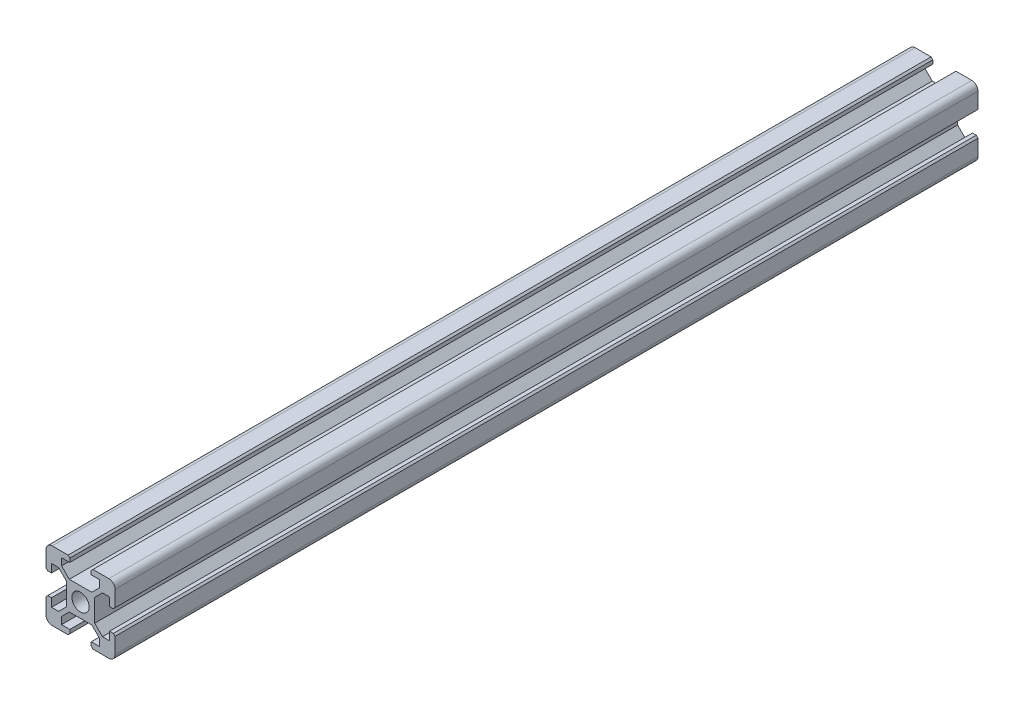
SolidWorks part; units mm, degrees
ref_plane "Front Plane" through (0, 0, 0) normal (0, 0, 1) x (1, 0, 0)
ref_plane "Top Plane" through (0, 0, 0) normal (0, 1, 0) x (1, 0, 0)
ref_plane "Right Plane" through (0, 0, 0) normal (1, 0, 0) x (0, 0, -1)
other "Default"
sketch "Sketch1" plane through (0, 0, 0) normal (0, 0, 1) x (1, 0, 0)
  line L0 (0, 4.1) -> (3.2515, 4.1)
  line L1 (3.2515, 4.1) -> (5.5, 6.3485)
  line L2 (5.5, 6.3485) -> (5.5, 8.4)
  line L3 (5.5, 8.4) -> (3.1, 8.4)
  line L4 (3.1, 8.4) -> (3.1, 9.5)
  line L5 (3.1, 9.5) -> (3.6, 10)
  line L6 (3.6, 10) -> (8.21, 10)
  line L7 (0, 0) -> (38.0854, 38.0854) construction
  line L8 (0, 0) -> (-25.3528, 25.3528) construction
  line L9 (0, 0) -> (34.3199, 0) construction
  line L10 (0, 0) -> (0, 57.4148) construction
  line L11 (1.7678, 1.7678) -> (9.4757, 9.4757)
  line L12 (0, 4.1) -> (0, 2.5)
  line L13 (10.0067, 8.9448) -> (12.1533, 6.7981) construction
  circle A0 centre (0, 0) radius 2.5 construction
  arc A1 (8.21, 10) -> (9.4757, 9.4757) centre (8.21, 8.21) cw
  arc A2 (0, 2.5) -> (1.7678, 1.7678) centre (0, 0) cw
  arc A3 (9.4757, 9.4757) -> (10, 8.21) centre (8.21, 8.21) cw construction
  dimension "HoleDiameter" = 5
  dimension "D1" = 45
  dimension "SlotWidth" = 6.2
  dimension "SlotWidthChamfer" = 7.2
  dimension "SlotHeight" = 4.3
  dimension "Width" = 20
  dimension "Height" = 20
  dimension "SlotInsideWidth" = 11
  dimension "ExtensionThickness" = 1.2
  dimension "SlotDepth" = 1.6
  dimension "D11" = 26.8014
extrude "Boss-Extrude1" add sketch "Sketch1" along normal mid plane 250
mirror "Mirror1" about plane through (1.7678, 1.7678, 125) normal (-0.7071, 0.7071, 0) of bodies 101
mirror "Mirror2" about plane through (0, 4.1, 125) normal (1, 0, 0) of bodies 102
mirror "Mirror3" about plane through (-4.1, 0, 125) normal (0, 1, 0) of bodies 103
